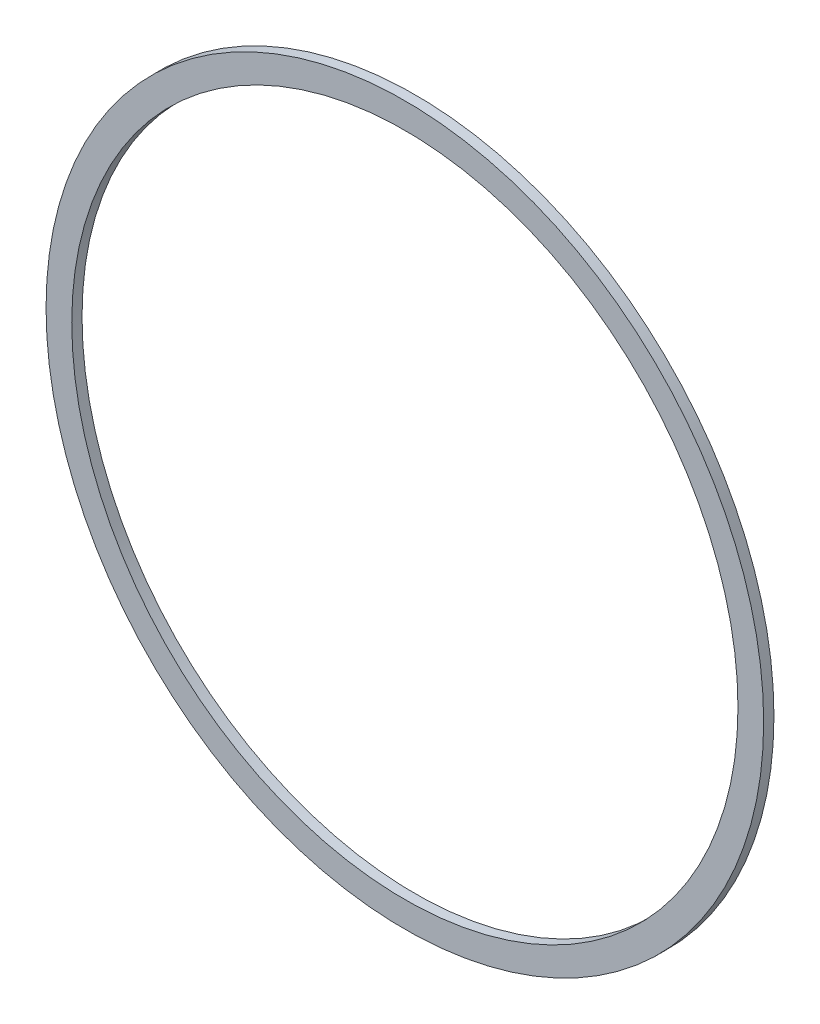
SolidWorks part; units mm, degrees
ref_plane "Front Plane" through (0, 0, 0) normal (0, 0, 1) x (1, 0, 0)
ref_plane "Top Plane" through (0, 0, 0) normal (0, 1, 0) x (1, 0, 0)
ref_plane "Right Plane" through (0, 0, 0) normal (1, 0, 0) x (0, 0, -1)
sketch "Sketch1" plane through (0, 0, 0) normal (0, 0, 1) x (1, 0, 0)
  circle A0 centre (0, 0) radius 64.8
  circle A1 centre (0, 0) radius 69.8
extrude "Boss-Extrude1" add sketch "Sketch1" along normal blind 2
